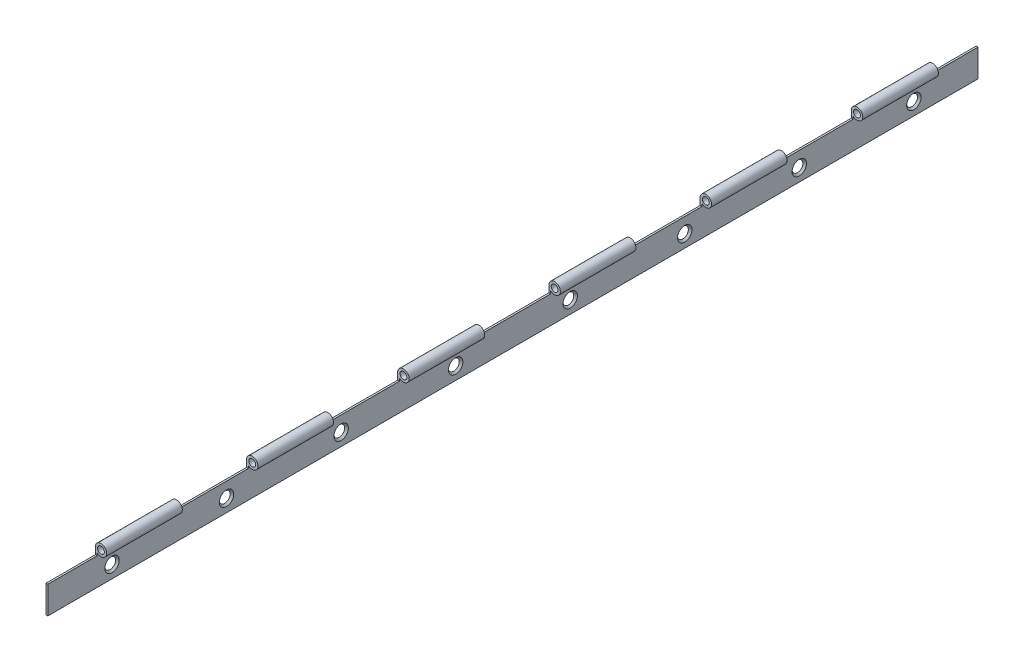
SolidWorks part; units mm, degrees
material "镀铬不锈钢"
ref_plane "前视基准面" through (0, 0, 0) normal (0, 0, 1) x (1, 0, 0)
ref_plane "上视基准面" through (0, 0, 0) normal (0, 1, 0) x (1, 0, 0)
ref_plane "右视基准面" through (0, 0, 0) normal (1, 0, 0) x (0, 0, -1)
sketch "草图1" plane through (0, 0, 0) normal (0, 0, 1) x (1, 0, 0)
  line L0 (0, 0) -> (0, 15)
  dimension "D1" = 15
extrude "拉伸-薄壁1" add sketch "草图1" along normal mid plane 406 thin
sketch "草图2" plane through (0, 0, 203) normal (0, 0, 1) x (1, 0, 0)
  line L0 (0, 0) -> (0, 15) construction
  line L1 (0, 15) -> (0.8, 15) construction
  circle A0 centre (2.5, 15) radius 2.5
  dimension "D1" = 5
sweep "扫描1" add profiles "草图2" path edge at (0.8, 15, 0)
sketch "草图3" plane through (0, 0, 203) normal (0, 0, 1) x (1, 0, 0)
  circle A0 centre (2.5, 15) radius 1.5
  dimension "D1" = 3
extrude "切除-拉伸1" cut sketch "草图3" against normal through all
sketch "草图10" plane through (0.8, 0, 0) normal (1, 0, 0) x (0, 0, -1)
  line L0 (-195, 12) -> (-165, 12) [skipped]
  line L1 (-129, 12) -> (-99, 12) [skipped]
  line L2 (-63, 18) -> (-33, 18) [skipped]
  line L3 (-129, 18) -> (-99, 18) [skipped]
  line L4 (-115.5, 18) -> (-115.5, 12)
  line L5 (-49.5, 18) -> (-49.5, 12) [skipped]
  line L6 (-63, 12) -> (-33, 12) [skipped]
  line L7 (3, 18) -> (33, 18) [skipped]
  line L8 (-16.5, 18) -> (-16.5, 12) [skipped]
  line L9 (16.5, 18) -> (16.5, 12) [skipped]
  line L10 (-181.5, 18) -> (-181.5, 12)
  line L11 (-148.5, 18) -> (-148.5, 12)
  line L12 (3, 12) -> (33, 12) [skipped]
  line L13 (69, 18) -> (99, 18) [skipped]
  line L14 (49.5, 18) -> (49.5, 12) [skipped]
  line L15 (82.5, 18) -> (82.5, 12) [skipped]
  line L16 (69, 12) -> (99, 12) [skipped]
  line L17 (135, 18) -> (165, 18) [skipped]
  line L18 (115.5, 18) -> (115.5, 12) [skipped]
  line L19 (148.5, 18) -> (148.5, 12) [skipped]
  line L20 (135, 12) -> (165, 12) [skipped]
  line L21 (201, 18) -> (231, 18) [skipped]
  line L22 (-49.5, 18.0062) -> (-49.5, 12.0062)
  line L23 (214.5, 18) -> (214.5, 12) [skipped]
  line L24 (201, 12) -> (231, 12) [skipped]
  line L25 (-181.5, 18) -> (-203, 18)
  line L26 (247.5, 18) -> (247.5, 12) [skipped]
  line L27 (-82.5, 18) -> (-82.5, 12) [skipped]
  line L28 (-195, 18) -> (-165, 18) [skipped]
  line L29 (-203, 18) -> (-203, 12)
  line L30 (-203, 0) -> (-203, 13.167) construction
  line L31 (-203, 12) -> (-181.5, 12)
  line L32 (-148.5, 18) -> (-115.5, 18)
  line L33 (-148.5, 12) -> (-115.5, 12)
  line L34 (-82.5, 18.0062) -> (-82.5, 12.0062)
  line L35 (-82.5, 18.0062) -> (-49.5, 18.0062)
  line L36 (-82.5, 12.0062) -> (-49.5, 12.0062)
  line L37 (16.5, 18.0123) -> (16.5, 12.0123)
  line L38 (-16.5, 18.0123) -> (-16.5, 12.0123)
  line L39 (-16.5, 18.0123) -> (16.5, 18.0123)
  line L40 (-16.5, 12.0123) -> (16.5, 12.0123)
  line L41 (82.5, 18.0185) -> (82.5, 12.0185)
  line L42 (49.5, 18.0185) -> (49.5, 12.0185)
  line L43 (49.5, 18.0185) -> (82.5, 18.0185)
  line L44 (49.5, 12.0185) -> (82.5, 12.0185)
  line L45 (148.5, 18.0247) -> (148.5, 12.0247)
  line L46 (115.5, 18.0247) -> (115.5, 12.0247)
  line L47 (115.5, 18.0247) -> (148.5, 18.0247)
  line L48 (181.5, 18) -> (181.5, 12) [skipped]
  line L49 (115.5, 12.0247) -> (148.5, 12.0247)
  line L50 (203, 12.0308) -> (203, 18.0308)
  line L51 (181.5, 18.0308) -> (181.5, 12.0308)
  line L52 (181.5, 18.0308) -> (203, 18.0308)
  line L53 (181.5, 12.0308) -> (203, 12.0308)
  line L54 (214.5, 18.0308) -> (214.5, 12.0308) [skipped]
  line L55 (203, 0) -> (203, 13.167) construction
  dimension "D1" = 33
  dimension "D2" = 21.5
  dimension "D3" = 33
  dimension "D4" = 33
  dimension "D5" = 6
  dimension "D6" = 33
extrude "切除-拉伸4" cut sketch "草图10" against normal mid plane 120
hole_wizard "M3 锥坑平头螺钉的锥形沉头孔1" positions "草图12" profile "草图11" countersink size "M3" standard "ISO" end condition through all
sketch "草图12" plane through (0.8, 0, 0) normal (1, 0, 0) x (0, 0, -1)
  line L0 (-203, 0) -> (203, 0) construction
  line L1 (203, 0) -> (203, 12.0308) construction
  point P0 (175, 5.5)
  point P3 (203, 6.0154)
  dimension "D1" = 5.5
  dimension "D2" = 28
sketch "草图11" plane through (0.8, 5.5, -175) normal (0, 1, 0) x (0, 0, -1)
  line L0 (0, 0) -> (0, 0.8)
  line L1 (0, 0.8) -> (1.7, 0.8)
  line L2 (1.7, 0.8) -> (1.7, 1.45)
  line L3 (1.7, 1.45) -> (3.15, 0)
  line L5 (3.15, 0) -> (0, 0)
  line L6 (-1.7, 1.45) -> (-3.15, 0) construction
  line L11 (0, -6.35) -> (0, 107.95) construction
  dimension "Í¨¿×¿×Ö±¾¶" = 3.4
  dimension "Í¨¿×¿×Éî¶È" = 0.8
  dimension "½ü¶Ë×¶ÐÎ³ÁÍ·¿×Ö±¾¶" = 6.3
  dimension "½ü¶Ë×¶ÐÎ³ÁÍ·¿×½Ç¶È" = 90
pattern_linear "阵列(线性)1" count 8 spacing 50 along (0, 0, 1) of "M3 锥坑平头螺钉的锥形沉头孔1"
